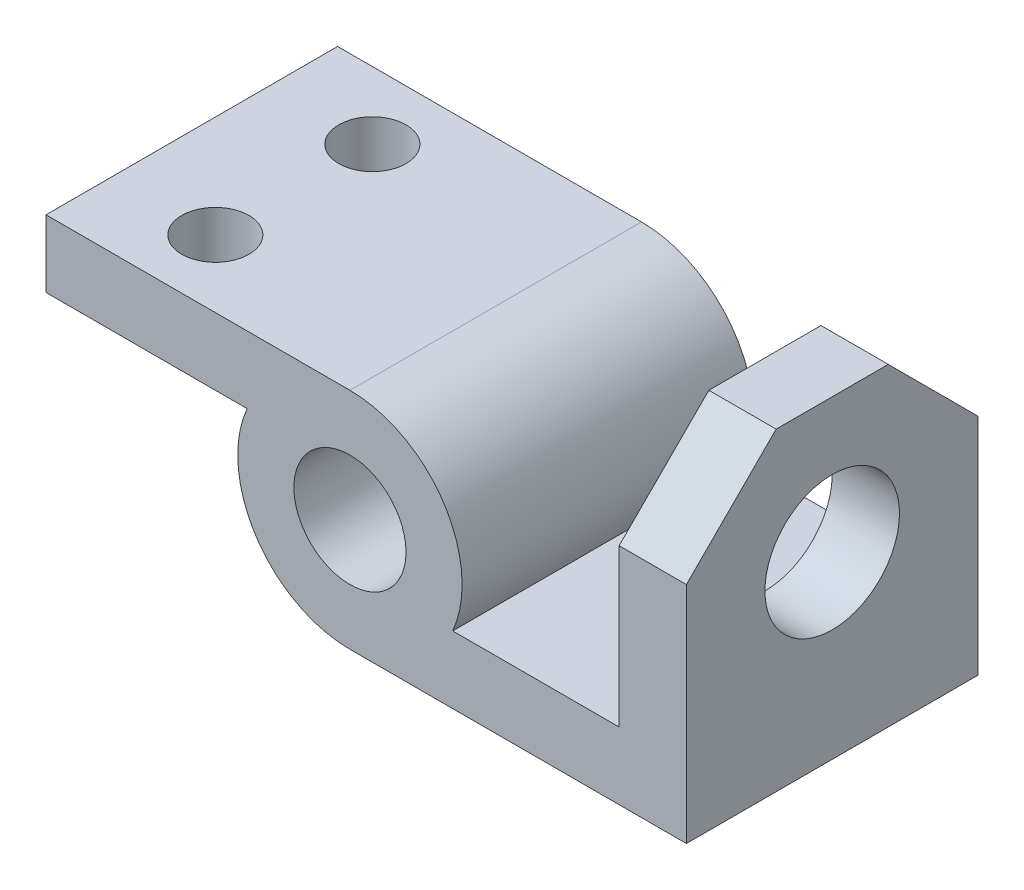
SolidWorks part; units mm, degrees
ref_plane "Front Plane" through (0, 0, 0) normal (0, 0, 1) x (1, 0, 0)
ref_plane "Top Plane" through (0, 0, 0) normal (0, 1, 0) x (1, 0, 0)
ref_plane "Right Plane" through (0, 0, 0) normal (1, 0, 0) x (0, 0, -1)
sketch "Sketch3" plane through (0, 0, 0) normal (0, 0, 1) x (1, 0, 0)
  line L0 (0, 1.25) -> (-3.3875, 1.25)
  line L1 (-3.3875, 1.25) -> (-3.3875, 0.5)
  line L2 (-3.3875, 0.5) -> (-1.1456, 0.5)
  line L3 (0, -1.25) -> (3.75, -1.25)
  line L4 (3.75, -1.25) -> (3.75, -0.5)
  line L5 (3.75, -0.5) -> (1.1456, -0.5)
  arc A0 (-1.1456, 0.5) -> (0, -1.25) centre (0, 0) ccw
  arc A1 (1.1456, -0.5) -> (0, 1.25) centre (0, 0) ccw
  dimension "D1" = 2.5
  dimension "D2" = 3.75
  dimension "D3" = 3.3875
  dimension "D4" = 0.75
extrude "Boss-Extrude2" add sketch "Sketch3" along normal mid plane 3.25
sketch "Sketch4" plane through (3.75, 0, 0) normal (1, 0, 0) x (0, 0, -1)
  line L0 (-1.625, -1.25) -> (-1.625, -0.5) construction
  line L1 (1.625, -1.25) -> (-1.625, -1.25)
  line L2 (1.625, -1.25) -> (1.625, 2.25)
  line L3 (1.625, 2.25) -> (-1.625, 2.25)
  line L4 (-1.625, -1.25) -> (-1.625, 2.25)
  dimension "D1" = 3.5
extrude "Boss-Extrude3" add sketch "Sketch4" against normal blind 0.75
chamfer "Chamfer1" distance 1 angle 45 2 edges at (3.375, 2.25, -1.625) (3.375, 2.25, 1.625)
hole_wizard "Ø1.25 (1.25) Diameter Hole1" positions "3DSketch1" profile "Sketch5" hole size "Ø1.25" standard "ISO" end condition up to next
sketch3d "3DSketch1"
  arc A0 (-1.1456, 0.5, 1.625) -> (0, -1.25, 1.625) centre (0, 0, 1.625) ccw construction
  point P0 (0, 0, 1.625)
  point P6 (0, 0, 2.875)
sketch "Sketch5" plane through (0, 0, 1.625) normal (1, 0, 0) x (0, -1, 0)
  line L0 (0, 0) -> (0, 3.25)
  line L1 (0, 3.25) -> (0.625, 3.25)
  line L2 (0.625, 3.25) -> (0.625, 0)
  line L5 (0.625, 0) -> (0, 0)
  line L11 (0, -6.35) -> (0, 107.95) construction
  dimension "Thru Hole Dia." = 1.25
  dimension "Thru Hole Depth" = 3.25
hole_wizard "Ø1.5 (1.5) Diameter Hole1" positions "Sketch6" profile "Sketch7" hole size "Ø1.5" standard "ISO"
sketch "Sketch6" plane through (3.75, 0, 0) normal (1, 0, 0) x (0, 0, -1)
  line L0 (-1.625, -1.25) -> (1.625, -1.25) construction
  point P0 (0, 0.75)
  point P5 (0, 0)
  dimension "D1" = 2
sketch "Sketch7" plane through (3.75, 0.75, 0) normal (0, 1, 0) x (0, 0, -1)
  line L0 (0, 0) -> (0, 0.75)
  line L1 (0, 0.75) -> (0.75, 0.75)
  line L2 (0.75, 0.75) -> (0.75, 0)
  line L5 (0.75, 0) -> (0, 0)
  line L11 (0, -6.35) -> (0, 107.95) construction
  dimension "Thru Hole Dia." = 1.5
  dimension "Thru Hole Depth" = 0.75
hole_wizard "Ø0.75 (0.75) Diameter Hole1" positions "Sketch8" profile "Sketch9" hole size "Ø0.75" standard "ISO" end condition up to next
sketch "Sketch8" plane through (0, 1.25, 0) normal (0, 1, 0) x (1, 0, 0)
  point P0 (-2.25, 0.875)
  dimension "D1" = 2.25
  dimension "D2" = 0.875
sketch "Sketch9" plane through (-2.25, 1.25, -0.875) normal (1, 0, 0) x (0, 0, 1)
  line L0 (0, 0) -> (0, 0.751)
  line L1 (0, 0.751) -> (0.375, 0.751)
  line L2 (0.375, 0.751) -> (0.375, 0)
  line L5 (0.375, 0) -> (0, 0)
  line L11 (0, -6.35) -> (0, 107.95) construction
  dimension "Thru Hole Dia." = 0.75
  dimension "Thru Hole Depth" = 0.751
mirror "Mirror1" about plane through (0, 0, 0) normal (0, 0, 1) of "Ø0.75 (0.75) Diameter Hole1"
